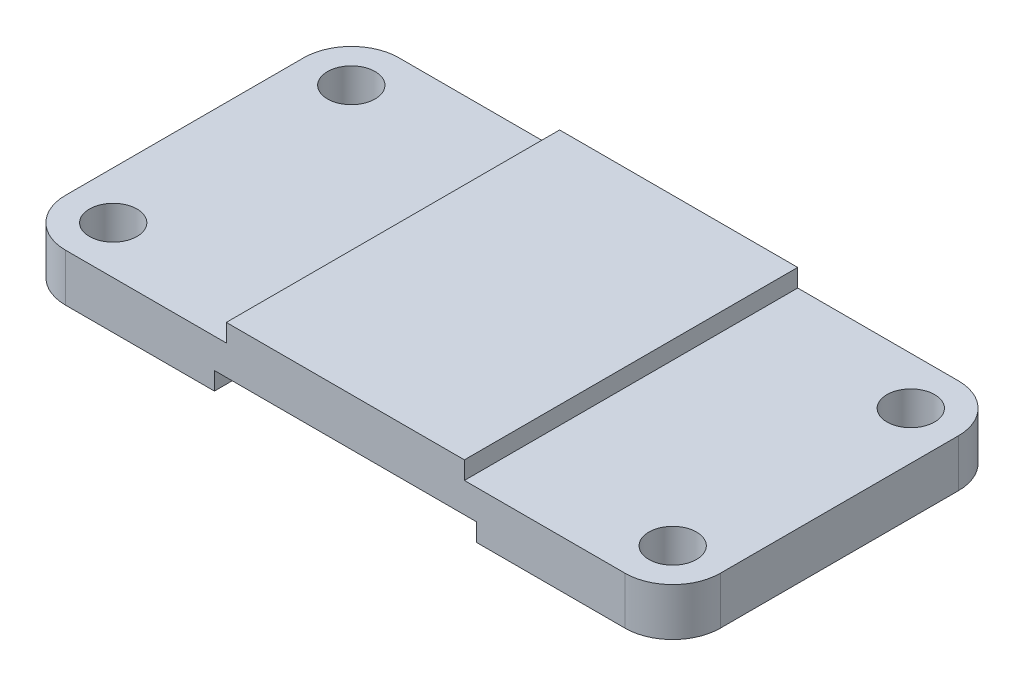
SolidWorks part; units mm, degrees
ref_plane "Ön Düzlem" through (0, 0, 0) normal (0, 0, 1) x (1, 0, 0)
ref_plane "Üst Düzlem" through (0, 0, 0) normal (0, 1, 0) x (1, 0, 0)
ref_plane "Sağ Düzlem" through (0, 0, 0) normal (1, 0, 0) x (0, 0, -1)
sketch "Çizim1" plane through (0, 0, 0) normal (0, 1, 0) x (1, 0, 0)
  line L1 (-470, -280) -> (470, -280)
  line L2 (-550, -200) -> (-550, 200)
  line L3 (-470, 280) -> (470, 280)
  line L4 (550, -200) -> (550, 200)
  line L5 (-550, -280) -> (550, 280) construction
  line L6 (-550, 280) -> (550, -280) construction
  arc A0 (-550, 200) -> (-470, 280) centre (-470, 200) cw
  arc A1 (-470, -280) -> (-550, -200) centre (-470, -200) cw
  arc A2 (470, -280) -> (550, -200) centre (470, -200) ccw
  arc A3 (470, 280) -> (550, 200) centre (470, 200) cw
  circle A4 centre (-470, 200) radius 40
  circle A5 centre (-470, -200) radius 40
  circle A6 centre (470, -200) radius 40
  circle A7 centre (470, 200) radius 40
  point P0 (0, 0)
  dimension "D3" = 80
  dimension "D4" = 80
  dimension "D1" = 1100
  dimension "D2" = 560
extrude "Yükseklik-Ekstrüzyon1" add sketch "Çizim1" along normal blind 80
sketch "Çizim2" plane through (0, 0, 280) normal (0, 0, 1) x (1, 0, 0)
  line L0 (-220, 0) -> (-220, 30)
  line L1 (-220, 0) -> (220, 0)
  line L2 (0, 0) -> (0, 30) construction
  line L3 (-220, 30) -> (220, 30)
  line L4 (220, 0) -> (220, 30)
  dimension "D1" = 220
  dimension "D2" = 30
extrude "Kes-Ekstrüzyon1" cut sketch "Çizim2" against normal through all
sketch "Çizim3" plane through (0, 0, 280) normal (0, 0, 1) x (1, 0, 0)
  line L0 (-470, 80) -> (470, 80) construction
  line L1 (-200, 80) -> (200, 80)
  line L2 (0, 80) -> (0, 110) construction
  line L3 (-200, 110) -> (200, 110)
  line L4 (200, 80) -> (200, 110)
  line L5 (-200, 80) -> (-200, 110)
  dimension "D1" = 200
  dimension "D2" = 30
extrude "Yükseklik-Ekstrüzyon2" add sketch "Çizim3" against normal up to vertex (560 mm away)
